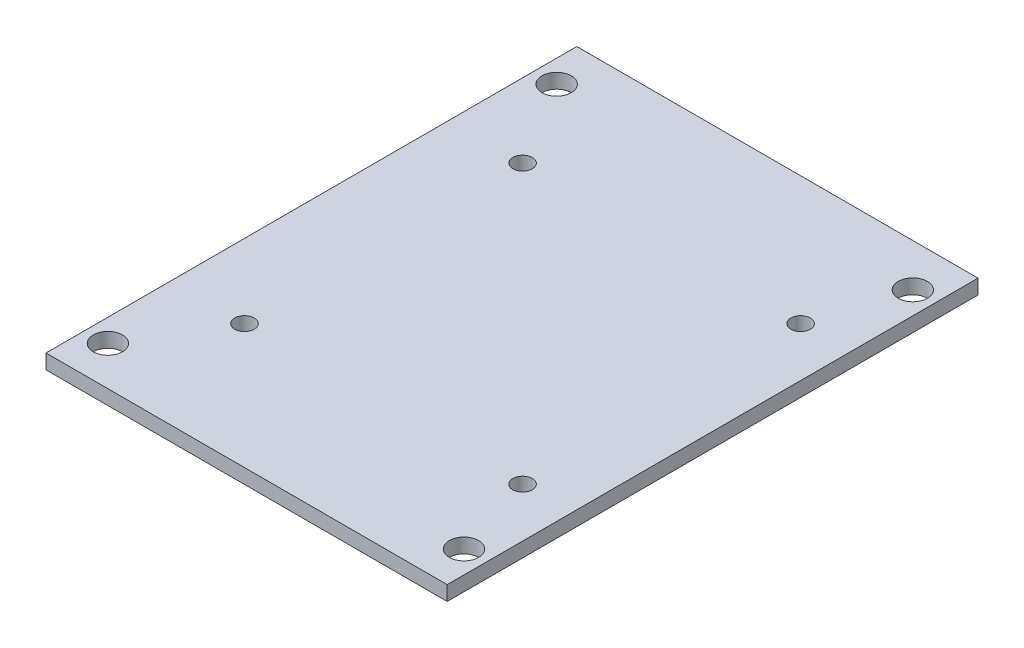
SolidWorks part; units mm, degrees
material "电源线路板"
ref_plane "前视基准面" through (0, 0, 0) normal (0, 0, 1) x (1, 0, 0)
ref_plane "上视基准面" through (0, 0, 0) normal (0, 1, 0) x (1, 0, 0)
ref_plane "右视基准面" through (0, 0, 0) normal (1, 0, 0) x (0, 0, -1)
other "Configuration Table"
sketch "草图1" plane through (0, 0, 0) normal (0, 1, 0) x (1, 0, 0)
  line L1 (14.25, -14.25) -> (-14.25, -14.25) construction
  line L2 (14.25, -14.25) -> (14.25, 14.25) construction
  line L3 (14.25, 14.25) -> (-14.25, 14.25) construction
  line L4 (-14.25, -14.25) -> (-14.25, 14.25) construction
  line L5 (14.25, -14.25) -> (-14.25, 14.25) construction
  line L6 (14.25, 14.25) -> (-14.25, -14.25) construction
  line L7 (-21.819, 27.381) -> (19.304, 27.381)
  line L8 (-21.819, 27.381) -> (-21.819, -27.026)
  line L9 (-21.819, -27.026) -> (19.304, -27.026)
  line L10 (19.304, 27.381) -> (19.304, -27.026)
  circle A0 centre (-14.25, 14.25) radius 1
  circle A1 centre (14.25, 14.25) radius 1
  circle A2 centre (14.25, -14.25) radius 1
  circle A3 centre (-14.25, -14.25) radius 1
  circle A4 centre (-19.5, 23) radius 1.5
  circle A5 centre (17, 23) radius 1.5
  circle A6 centre (17, -23) radius 1.5
  circle A7 centre (-19.5, -23) radius 1.5
  point P0 (0, 0)
  point P20 (0, 0)
  dimension "D3" = 2
  dimension "D5" = 46
  dimension "D6" = 3
  dimension "D7" = 3
  dimension "D8" = 3
  dimension "D9" = 3
  dimension "D10" = 46
  dimension "D11" = 36.5
  dimension "D12" = 36.5
  dimension "D13" = 23
  dimension "D14" = 17
  dimension "D1" = 28.5
  dimension "D2" = 28.5
  dimension "D15" = 21.819
  dimension "D16" = 19.304
  dimension "D17" = 27.381
  dimension "D18" = 27.026
  dimension "D4" = 4
extrude "凸台-拉伸1" add sketch "草图1" along normal blind 1.5
